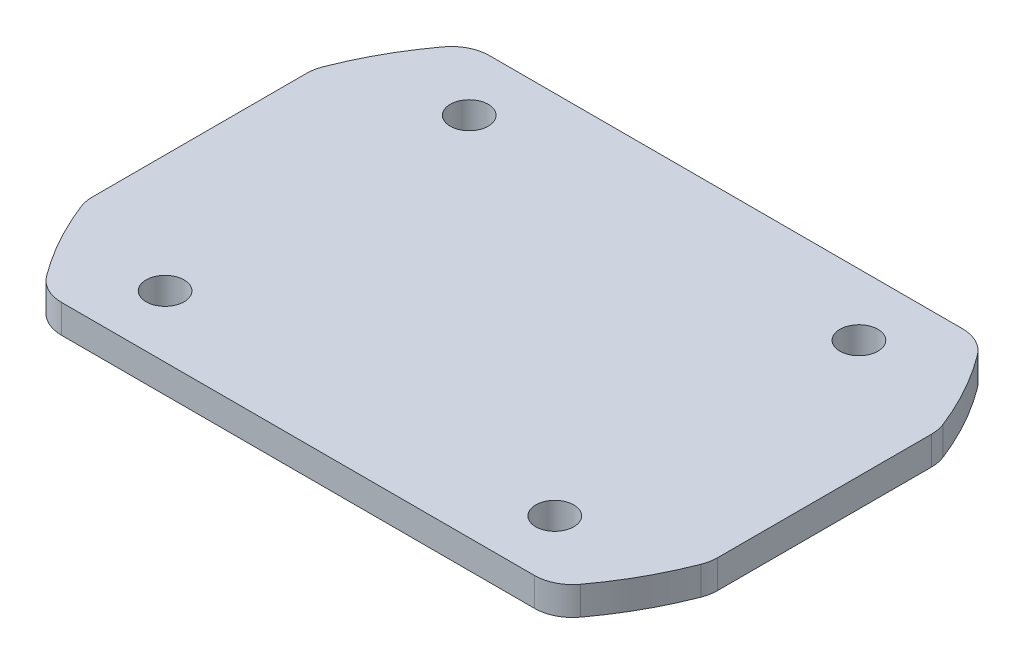
SolidWorks part; units mm, degrees
ref_plane "前视基准面" through (0, 0, 0) normal (0, 0, 1) x (1, 0, 0)
ref_plane "上视基准面" through (0, 0, 0) normal (0, 1, 0) x (1, 0, 0)
ref_plane "右视基准面" through (0, 0, 0) normal (1, 0, 0) x (0, 0, -1)
sketch "草图1" plane through (0, 0, 0) normal (0, 1, 0) x (1, 0, 0)
  line L0 (0, -55) -> (0, 55) construction
  line L1 (-55, 0) -> (55, 0) construction
  line L2 (-13.4048, 11.25) -> (13.4048, 11.25)
  line L3 (-13.4048, -11.25) -> (13.4048, -11.25)
  line L5 (-16.4393, 6) -> (-16.4393, -6)
  line L6 (16.4393, 6) -> (16.4393, -6)
  arc A0 (-13.4048, 11.25) -> (-16.4393, 6) centre (0, 0) ccw
  circle A4 centre (10.25, -8) radius 1
  circle A9 centre (-10.25, -8) radius 1
  circle A10 centre (-10.25, 8) radius 1
  circle A11 centre (10.25, 8) radius 1
  circle A12 centre (-14.75, 0) radius 1.25 construction
  circle A13 centre (14.75, 0) radius 1.25 construction
  arc A14 (13.4048, -11.25) -> (16.4393, -6) centre (0, 0) ccw
  arc A15 (-16.4393, -6) -> (-13.4048, -11.25) centre (0, 0) ccw
  arc A16 (16.4393, 6) -> (13.4048, 11.25) centre (0, 0) ccw
  dimension "D1" = 35
  dimension "D2" = 20.5
  dimension "D3" = 2
  dimension "D4" = 16
  dimension "D5" = 2.5
  dimension "D7" = 22.5
  dimension "D6" = 29.5
  dimension "D8" = 12
extrude "凸台-拉伸1" add sketch "草图1" along normal blind 1.5
fillet "圆角1" radius 2 8 edges at (-13.4048, 0.75, -11.25) (13.4048, 0.75, -11.25) (16.4393, 0.75, -6) (16.4393, 0.75, 6) (13.4048, 0.75, 11.25) (-13.4048, 0.75, 11.25) (-16.4393, 0.75, 6) (-16.4393, 0.75, -6)
